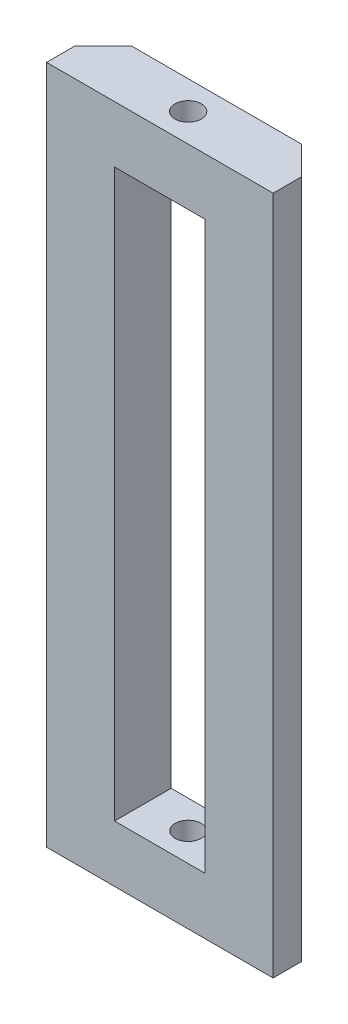
SolidWorks part; units mm, degrees
ref_plane "Спереди" through (0, 0, 0) normal (0, 0, 1) x (1, 0, 0)
ref_plane "Сверху" through (0, 0, 0) normal (0, 1, 0) x (1, 0, 0)
ref_plane "Справа" through (0, 0, 0) normal (1, 0, 0) x (0, 0, -1)
ref_plane "Плоскость4" through (0, 116.196, 0) normal (0, 1, 0) x (1, 0, 0)
sketch "Эскиз1" plane through (0, 116.196, 0) normal (0, 1, 0) x (1, 0, 0)
  line L0 (44.809, -48.2731) -> (84.809, -48.2731)
  line L1 (84.809, -48.2731) -> (84.809, -38.2731)
  line L2 (84.809, -38.2731) -> (44.809, -38.2731)
  line L3 (44.809, -38.2731) -> (44.809, -48.2731)
  circle A0 centre (64.809, -43.2731) radius 2.3
extrude "Бобышка-Вытянуть1" add sketch "Эскиз1" along normal blind 10
ref_plane "Плоскость5" through (0, 126.196, 0) normal (0, 1, 0) x (1, 0, 0)
sketch "Эскиз2" plane through (0, 126.196, 0) normal (0, 1, 0) x (1, 0, 0)
  line L0 (44.809, -38.2731) -> (44.809, -48.2731)
  line L2 (84.809, -48.2731) -> (84.809, -38.2731)
  line L4 (44.809, -38.2731) -> (56.809, -38.2731)
  line L5 (84.809, -38.2731) -> (44.809, -38.2731) construction
  line L6 (56.809, -38.2731) -> (56.809, -48.2731)
  line L7 (44.809, -48.2731) -> (84.809, -48.2731) construction
  line L8 (56.809, -48.2731) -> (44.809, -48.2731)
  line L9 (84.809, -38.2731) -> (72.809, -38.2731)
  line L10 (72.809, -38.2731) -> (72.809, -48.2731)
  line L11 (72.809, -48.2731) -> (84.809, -48.2731)
extrude "Бобышка-Вытянуть3" add sketch "Эскиз2" along normal blind 100
ref_plane "Плоскость6" through (0, 226.196, 0) normal (0, 1, 0) x (1, 0, 0)
sketch "Эскиз3" plane through (0, 226.196, 0) normal (0, 1, 0) x (1, 0, 0)
  line L0 (44.809, -38.2731) -> (44.809, -48.2731)
  line L1 (44.809, -48.2731) -> (84.809, -48.2731)
  line L2 (84.809, -48.2731) -> (84.809, -38.2731)
  line L3 (84.809, -38.2731) -> (44.809, -38.2731)
  circle A0 centre (64.809, -43.2731) radius 2.3293
extrude "Бобышка-Вытянуть4" add sketch "Эскиз3" along normal blind 10
chamfer "Фаска1" distance 5 angle 45 2 edges at (84.809, 176.196, 38.2731) (44.809, 176.196, 38.2731)
